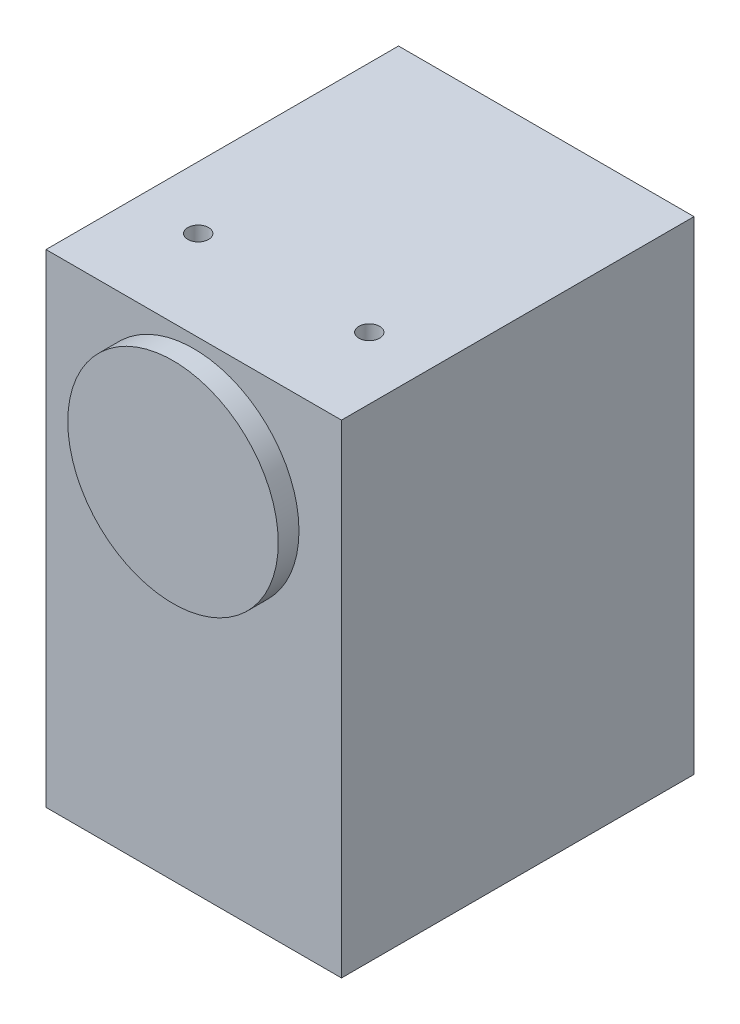
SolidWorks part; units mm, degrees
ref_plane "Plan de face" through (0, 0, 0) normal (0, 0, 1) x (1, 0, 0)
ref_plane "Plan de dessus" through (0, 0, 0) normal (0, 1, 0) x (1, 0, 0)
ref_plane "Plan de droite" through (0, 0, 0) normal (1, 0, 0) x (0, 0, -1)
sketch "Esquisse1" plane through (0, 0, 0) normal (0, 0, 1) x (1, 0, 0)
  line L1 (-14.25, -23.3) -> (14.25, -23.3)
  line L2 (-14.25, -23.3) -> (-14.25, 23.3)
  line L3 (-14.25, 23.3) -> (14.25, 23.3)
  line L4 (14.25, -23.3) -> (14.25, 23.3)
  line L5 (-14.25, -23.3) -> (14.25, 23.3) construction
  line L6 (-14.25, 23.3) -> (14.25, -23.3) construction
  point P0 (0, 0)
  dimension "D1" = 28.5
  dimension "D2" = 46.6
extrude "Boss.-Extru.1" add sketch "Esquisse1" along normal blind 34
sketch "Esquisse2" plane through (0, 0, 34) normal (0, 0, 1) x (1, 0, 0)
  line L0 (14.25, 23.3) -> (-14.25, 23.3) construction
  circle A0 centre (0, 12) radius 10.15
  dimension "D1" = 20.3
  dimension "D2" = 11.3
extrude "Boss.-Extru.2" add sketch "Esquisse2" along normal blind 2
sketch "Esquisse3" plane through (0, 23.3, 0) normal (0, 1, 0) x (1, 0, 0)
  line L3 (14.25, -34) -> (14.25, 0) construction
  circle A0 centre (-8.25, -25.3194) radius 1
  circle A1 centre (8.25, -25.3194) radius 1
  point P4 (0, 0)
  dimension "D1" = 2
  dimension "D2" = 16.5
  dimension "D3" = 6
extrude "Enlèv. mat.-Extru.1" cut sketch "Esquisse3" against normal blind 2
